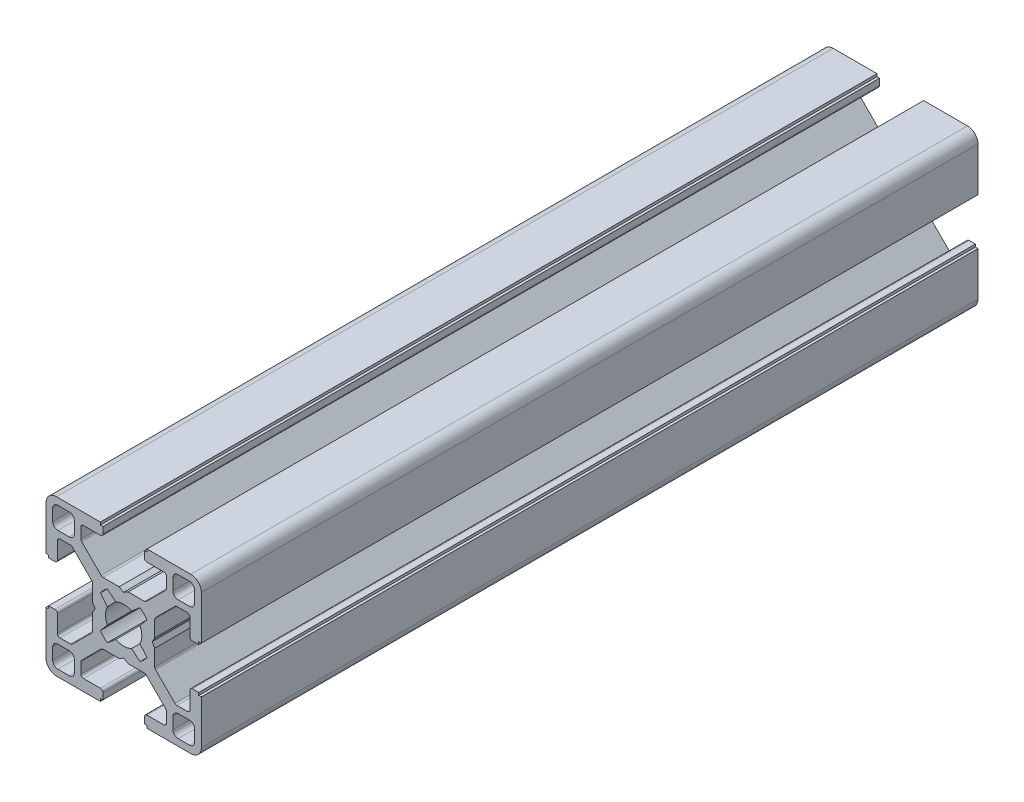
SolidWorks part; units mm, degrees
ref_plane "Front Plane" through (0, 0, 0) normal (0, 0, 1) x (1, 0, 0)
ref_plane "Top Plane" through (0, 0, 0) normal (0, 1, 0) x (1, 0, 0)
ref_plane "Right Plane" through (0, 0, 0) normal (1, 0, 0) x (0, 0, -1)
sketch "Sketch1" plane through (0, 0, 0) normal (0, 0, 1) x (1, 0, 0)
  line L0 (-15, 0) -> (15, 0) construction
  line L1 (0, -15) -> (0, 15) construction
  line L2 (-4.5, 15) -> (4.5, 15) construction
  line L3 (-4, -15) -> (4, -15) construction
  line L4 (-4.5, 15) -> (-4.5, 14.5)
  line L5 (-4.5, 14.5) -> (-4, 14.5)
  line L6 (-4, 14.5) -> (-4, 13.29)
  line L7 (-4.5, 12.79) -> (-7.7675, 12.79)
  line L8 (-8.2675, 12.29) -> (-8.2675, 10.2707)
  line L9 (-8.1211, 9.9171) -> (-4.3504, 6.1464)
  line L10 (-3.9968, 6) -> (0, 6)
  line L11 (0, 0) -> (-15, 15) construction
  line L12 (-4.5, 15) -> (-12.968, 15)
  line L14 (-12.705, 9.5135) -> (-10.5135, 9.5135)
  line L15 (-13.705, 10.5135) -> (-13.705, 12.705)
  line L16 (-12.705, 13.705) -> (-10.5135, 13.705)
  line L17 (-9.5135, 10.5135) -> (-9.5135, 12.705)
  line L18 (-13.705, 9.5135) -> (-9.5135, 13.705) construction
  line L19 (-13.705, 13.705) -> (-9.5135, 9.5135) construction
  line L20 (-3.1568, 4.5038) -> (-1.5303, 3.1477) construction
  line L21 (-4.5038, 3.1568) -> (-3.1477, 1.5303) construction
  line L22 (-6, 3.9968) -> (-6, 0)
  line L23 (-9.9171, 8.1211) -> (-6.1464, 4.3504)
  line L24 (-15, 4.5) -> (-15, 12.968)
  line L25 (-12.29, 8.2675) -> (-10.2707, 8.2675)
  line L26 (-12.79, 4.5) -> (-12.79, 7.7675)
  line L27 (-14.5, 4) -> (-13.29, 4)
  line L28 (-14.5, 4.5) -> (-14.5, 4)
  line L29 (-15, 4.5) -> (-14.5, 4.5)
  circle A0 centre (0, 0) radius 3.5
  arc A1 (-12.968, 15) -> (-15, 12.968) centre (-12.968, 12.968) ccw
  circle A2 centre (0, 0) radius 5.5 construction
  arc A3 (-10.5135, 9.5135) -> (-9.5135, 10.5135) centre (-10.5135, 10.5135) ccw
  arc A4 (-13.705, 12.705) -> (-12.705, 13.705) centre (-12.705, 12.705) cw
  arc A5 (-10.5135, 13.705) -> (-9.5135, 12.705) centre (-10.5135, 12.705) cw
  arc A6 (-12.705, 9.5135) -> (-13.705, 10.5135) centre (-12.705, 10.5135) cw
  arc A7 (-12.79, 4.5) -> (-13.29, 4) centre (-13.29, 4.5) cw
  arc A8 (-12.29, 8.2675) -> (-12.79, 7.7675) centre (-12.29, 7.7675) ccw
  arc A9 (-9.9171, 8.1211) -> (-10.2707, 8.2675) centre (-10.2707, 7.7675) ccw
  arc A10 (-6, 3.9968) -> (-6.1464, 4.3504) centre (-6.5, 3.9968) ccw
  arc A11 (-4.3504, 6.1464) -> (-3.9968, 6) centre (-3.9968, 6.5) ccw
  arc A12 (-4, 13.29) -> (-4.5, 12.79) centre (-4.5, 13.29) cw
  arc A13 (-7.7675, 12.79) -> (-8.2675, 12.29) centre (-7.7675, 12.29) ccw
  arc A14 (-8.2675, 10.2707) -> (-8.1211, 9.9171) centre (-7.7675, 10.2707) ccw
  point P4 (0, 0)
  point P8 (0, 0)
  point P13 (0, 15)
  point P15 (0, -15)
  point P16 (0, 6)
  point P23 (-11.6092, 11.6093)
  point P26 (0, 6)
  point P62 (-12.79, 4)
  point P65 (-12.79, 8.2675)
  point P68 (-10.0636, 8.2675)
  point P71 (-6, 4.2039)
  point P74 (-4.2039, 6)
  point P77 (-4, 12.79)
  point P80 (-8.2675, 12.79)
  point P83 (-8.2675, 10.0636)
  dimension "Center Hole Diameter" = 7
  dimension "D11" = 2.032
  dimension "D9" = 11
  dimension "D13" = 1
  dimension "D14" = 0.5
  dimension "Rail Height" = 30
  dimension "Rail Width" = 30
  dimension "T-Slot Width" = 8
  dimension "T-Slot Depth" = 9
  dimension "D1" = 9
  dimension "D2" = 45
  dimension "D3" = 8
  dimension "D4" = 2.21
  dimension "D5" = 16.535
  dimension "D7" = 2.54
  dimension "D6" = 1.295
  dimension "D8" = 1.246
  dimension "D10" = 10.36
  dimension "D12" = 1.905
sketch "Sketch2" plane through (0, 0, 0) normal (1, 0, 0) x (0, 0, -1)
  line L0 (-76.2, 0) -> (76.2, 0) construction
  line L2 (0, -15) -> (0, 15) construction
  line L3 (0, -15) -> (0, 15) construction
  line L4 (-76.2, -15) -> (-76.2, 15) construction
  line L5 (76.2, -15) -> (76.2, 15) construction
  point P0 (-38.7, 0)
  point P3 (0, 0)
  point P4 (38.7, 0)
  point P12 (-76.2, 0)
  point P14 (76.2, 0)
  dimension "Length" = 152.4
  dimension "D1" = 37.5
sketch "Sketch3" plane through (0, 0, 0) normal (0, 0, 1) x (1, 0, 0)
  line L0 (-4.5038, 3.1568) -> (-3.1477, 1.5303)
  line L1 (0, 3.5) -> (0, 5.5)
  line L2 (-5.5, 0) -> (-3.5, 0)
  line L7 (-6, 3.9968) -> (-6, 0) construction
  line L31 (-9.9171, 8.1211) -> (-6.1464, 4.3504) construction
  line L117 (-12.29, 8.2675) -> (-10.2707, 8.2675) construction
  line L118 (-12.79, 4.5) -> (-12.79, 7.7675) construction
  line L157 (-12.705, 9.5135) -> (-10.5135, 9.5135)
  line L158 (-9.5135, 10.5135) -> (-9.5135, 12.705)
  line L163 (-10.5135, 13.705) -> (-12.705, 13.705)
  line L164 (-13.705, 12.705) -> (-13.705, 10.5135)
  line L165 (-12.705, 9.5135) -> (-10.5135, 9.5135)
  line L166 (-9.5135, 10.5135) -> (-9.5135, 12.705)
  line L167 (-10.5135, 13.705) -> (-12.705, 13.705)
  line L168 (-13.705, 12.705) -> (-13.705, 10.5135)
  line L169 (-14.5, 4) -> (-13.29, 4) construction
  line L170 (-14.5, 4.5) -> (-14.5, 4) construction
  line L171 (-15, 4.5) -> (-14.5, 4.5) construction
  line L172 (-15, 4.5) -> (-15, 12.968) construction
  line L173 (-4.5, 15) -> (-12.968, 15) construction
  line L174 (-4.5, 15) -> (-4.5, 14.5) construction
  line L175 (-4.5, 14.5) -> (-4, 14.5) construction
  line L176 (-4, 14.5) -> (-4, 13.29) construction
  line L177 (-4.5, 12.79) -> (-7.7675, 12.79) construction
  line L178 (-8.2675, 12.29) -> (-8.2675, 10.2707) construction
  line L179 (-8.1211, 9.9171) -> (-4.3504, 6.1464) construction
  line L180 (-3.9968, 6) -> (0, 6) construction
  line L181 (-6, 3.9968) -> (-6, 0.866)
  line L182 (-9.9171, 8.1211) -> (-6.1464, 4.3504)
  line L183 (-12.29, 8.2675) -> (-10.2707, 8.2675)
  line L184 (-12.79, 4.5) -> (-12.79, 7.7675)
  line L185 (-14.5, 4) -> (-13.29, 4)
  line L186 (-14.5, 4.5) -> (-14.5, 4)
  line L187 (-15, 4.5) -> (-14.5, 4.5)
  line L188 (-15, 4.5) -> (-15, 12.968)
  line L189 (-4.5, 15) -> (-12.968, 15)
  line L190 (-4.5, 15) -> (-4.5, 14.5)
  line L191 (-4.5, 14.5) -> (-4, 14.5)
  line L192 (-4, 14.5) -> (-4, 13.29)
  line L193 (-4.5, 12.79) -> (-7.7675, 12.79)
  line L194 (-8.2675, 12.29) -> (-8.2675, 10.2707)
  line L195 (-8.1211, 9.9171) -> (-4.3504, 6.1464)
  line L196 (-3.9968, 6) -> (-0.866, 6)
  line L197 (-0.866, 6) -> (0, 5.5)
  line L198 (0, -15) -> (0, 15) construction
  line L199 (0, 0) -> (-15, 15) construction
  line L200 (0, 0) -> (-15, 15) construction
  line L201 (-3.1568, 4.5038) -> (-1.5303, 3.1477) construction
  line L202 (-3.1568, 4.5038) -> (-1.5303, 3.1477)
  line L203 (-6, 0.866) -> (-5.5, 0)
  line L204 (-15, 0) -> (15, 0) construction
  line L205 (-15, 0) -> (15, 0) construction
  line L206 (0, -15) -> (0, 15) construction
  arc A0 (-3.5, 0) -> (-3.1477, 1.5303) centre (0, 0) cw
  arc A10 (-6, 3.9968) -> (-6.1464, 4.3504) centre (-6.5, 3.9968) ccw construction
  circle A16 centre (0, 0) radius 3.5
  arc A18 (0, 3.5) -> (-1.5303, 3.1477) centre (0, 0) ccw
  arc A20 (-9.9171, 8.1211) -> (-10.2707, 8.2675) centre (-10.2707, 7.7675) ccw construction
  arc A22 (-12.29, 8.2675) -> (-12.79, 7.7675) centre (-12.29, 7.7675) ccw construction
  arc A28 (-13.29, 4) -> (-12.79, 4.5) centre (-13.29, 4.5) ccw construction
  arc A29 (-10.5135, 9.5135) -> (-9.5135, 10.5135) centre (-10.5135, 10.5135) ccw
  arc A30 (-9.5135, 12.705) -> (-10.5135, 13.705) centre (-10.5135, 12.705) ccw
  arc A31 (-12.705, 13.705) -> (-13.705, 12.705) centre (-12.705, 12.705) ccw
  arc A32 (-13.705, 10.5135) -> (-12.705, 9.5135) centre (-12.705, 10.5135) ccw
  arc A33 (-10.5135, 9.5135) -> (-9.5135, 10.5135) centre (-10.5135, 10.5135) ccw
  arc A34 (-9.5135, 12.705) -> (-10.5135, 13.705) centre (-10.5135, 12.705) ccw
  arc A35 (-12.705, 13.705) -> (-13.705, 12.705) centre (-12.705, 12.705) ccw
  arc A36 (-13.705, 10.5135) -> (-12.705, 9.5135) centre (-12.705, 10.5135) ccw
  arc A37 (-12.968, 15) -> (-15, 12.968) centre (-12.968, 12.968) ccw construction
  arc A38 (-4.5, 12.79) -> (-4, 13.29) centre (-4.5, 13.29) ccw construction
  arc A39 (-7.7675, 12.79) -> (-8.2675, 12.29) centre (-7.7675, 12.29) ccw construction
  arc A40 (-8.2675, 10.2707) -> (-8.1211, 9.9171) centre (-7.7675, 10.2707) ccw construction
  arc A41 (-4.3504, 6.1464) -> (-3.9968, 6) centre (-3.9968, 6.5) ccw construction
  arc A42 (-6, 3.9968) -> (-6.1464, 4.3504) centre (-6.5, 3.9968) ccw
  arc A43 (-9.9171, 8.1211) -> (-10.2707, 8.2675) centre (-10.2707, 7.7675) ccw
  arc A44 (-12.29, 8.2675) -> (-12.79, 7.7675) centre (-12.29, 7.7675) ccw
  arc A45 (-13.29, 4) -> (-12.79, 4.5) centre (-13.29, 4.5) ccw
  arc A46 (-12.968, 15) -> (-15, 12.968) centre (-12.968, 12.968) ccw
  arc A47 (-4.5, 12.79) -> (-4, 13.29) centre (-4.5, 13.29) ccw
  arc A48 (-7.7675, 12.79) -> (-8.2675, 12.29) centre (-7.7675, 12.29) ccw
  arc A49 (-8.2675, 10.2707) -> (-8.1211, 9.9171) centre (-7.7675, 10.2707) ccw
  arc A50 (-4.3504, 6.1464) -> (-3.9968, 6) centre (-3.9968, 6.5) ccw
  circle A51 centre (0, 0) radius 5.5 construction
  arc A52 (-3.1568, 4.5038) -> (-4.5038, 3.1568) centre (0, 0) ccw
  dimension "D3" = 60
  dimension "D4" = 60
  dimension "D1" = 0
  dimension "D2" = 0
extrude "Boss-Extrude1" add sketch "Sketch3" along normal mid plane 150
pattern_circular "CirPattern1" count 4 over 360 about axis through (0, 0, 0) along (0, 0, 1) of "Boss-Extrude1"
ref_plane "Contact Plane1" through (15, 0, 0) normal (1, 0, 0) x (0, 0, -1)
ref_plane "Contact Plane2" through (0, -15, 0) normal (0, 1, 0) x (1, 0, 0)
ref_plane "Contact Plane3" through (-15, 0, 0) normal (1, 0, 0) x (0, 0, -1)
ref_plane "Contact Plane4" through (0, 15, 0) normal (0, 1, 0) x (1, 0, 0)
equation "\"D1@Sketch2\" = \"Rail Height@Sketch1\" * 1.25"
equation "\"D1@Sketch1\"=\"T-Slot Width@Sketch1\"+1mm"
equation "\"D3@Sketch1\"=\"T-Slot Width@Sketch1\""
equation "\"D1@Boss-Extrude1\"=\"Length\""
equation "\"Length\"= 150mm"
